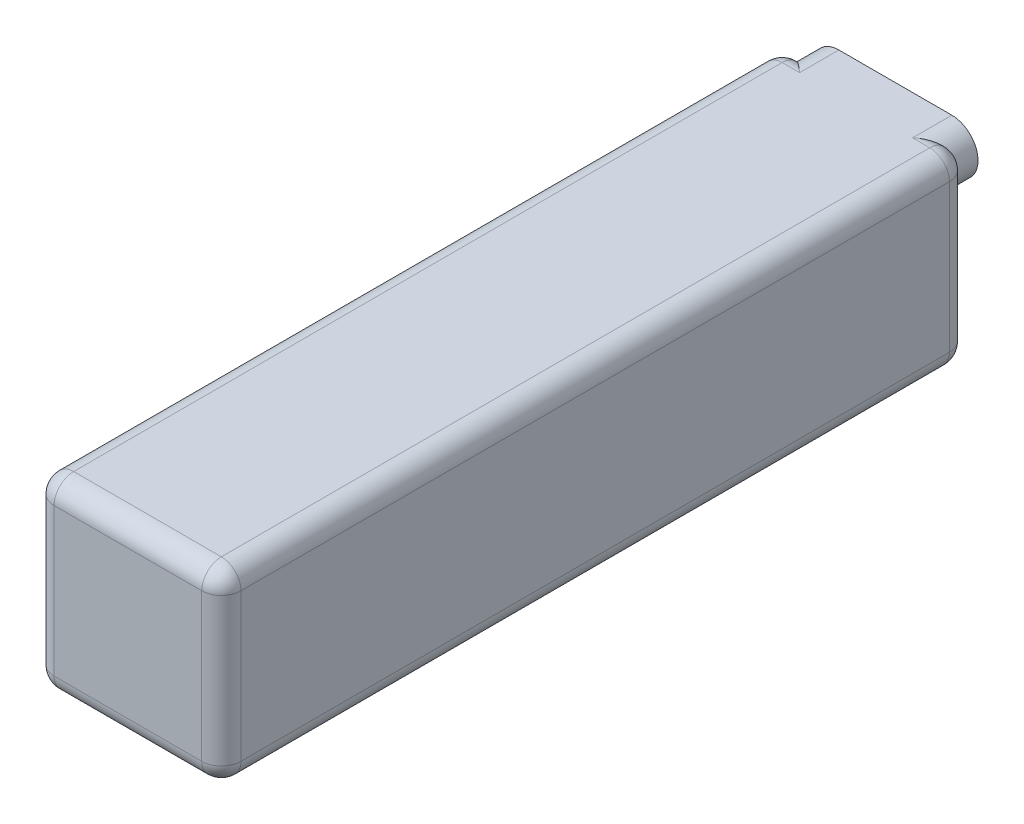
SolidWorks part; units mm, degrees
material "Custom Plastic"
ref_plane "Front Plane" through (0, 0, 0) normal (0, 0, 1) x (1, 0, 0)
ref_plane "Top Plane" through (0, 0, 0) normal (0, 1, 0) x (1, 0, 0)
ref_plane "Right Plane" through (0, 0, 0) normal (1, 0, 0) x (0, 0, -1)
sketch "Sketch1" plane through (0, 0, 0) normal (1, 0, 0) x (0, 0, -1)
  line L1 (-38.1, -9.525) -> (38.1, -9.525)
  line L2 (-38.1, -9.525) -> (-38.1, 9.525)
  line L3 (-38.1, 9.525) -> (38.1, 9.525)
  line L4 (38.1, -9.525) -> (38.1, 9.525)
  line L5 (-38.1, -9.525) -> (38.1, 9.525) construction
  line L6 (-38.1, 9.525) -> (38.1, -9.525) construction
  point P0 (0, 0)
  dimension "D1" = 76.2
  dimension "D2" = 19.05
extrude "Boss-Extrude1" add sketch "Sketch1" along normal mid plane 19.05
fillet "Fillet1" radius 2 12 edges at (-9.525, 0, 38.1) (0, -9.525, 38.1) (-9.525, -9.525, 0) (0, -9.525, -38.1) (-9.525, 0, -38.1) (9.525, -9.525, 0) (9.525, 0, 38.1) (9.525, 0, -38.1) (0, 9.525, -38.1) (9.525, 9.525, 0) (0, 9.525, 38.1) (-9.525, 9.525, 0)
sketch "Sketch2" plane through (0, 0, -38.1) normal (0, 0, -1) x (-1, 0, 0)
  line L0 (-5.7719, 6.858) -> (5.7397, 6.858) construction
  line L1 (-5.7719, 9.525) -> (5.7397, 9.525)
  line L2 (-5.7719, 4.191) -> (5.7397, 4.191)
  line L4 (-7.525, 9.525) -> (7.525, 9.525) construction
  arc A0 (-5.7719, 9.525) -> (-5.7719, 4.191) centre (-5.7719, 6.858) ccw
  arc A1 (5.7397, 4.191) -> (5.7397, 9.525) centre (5.7397, 6.858) ccw
  point P2 (-0.0161, 6.858)
  dimension "D1" = 5.334
extrude "Boss-Extrude2" add sketch "Sketch2" along normal blind 2 and the other way up to next contours L2 A1 L1 A0
